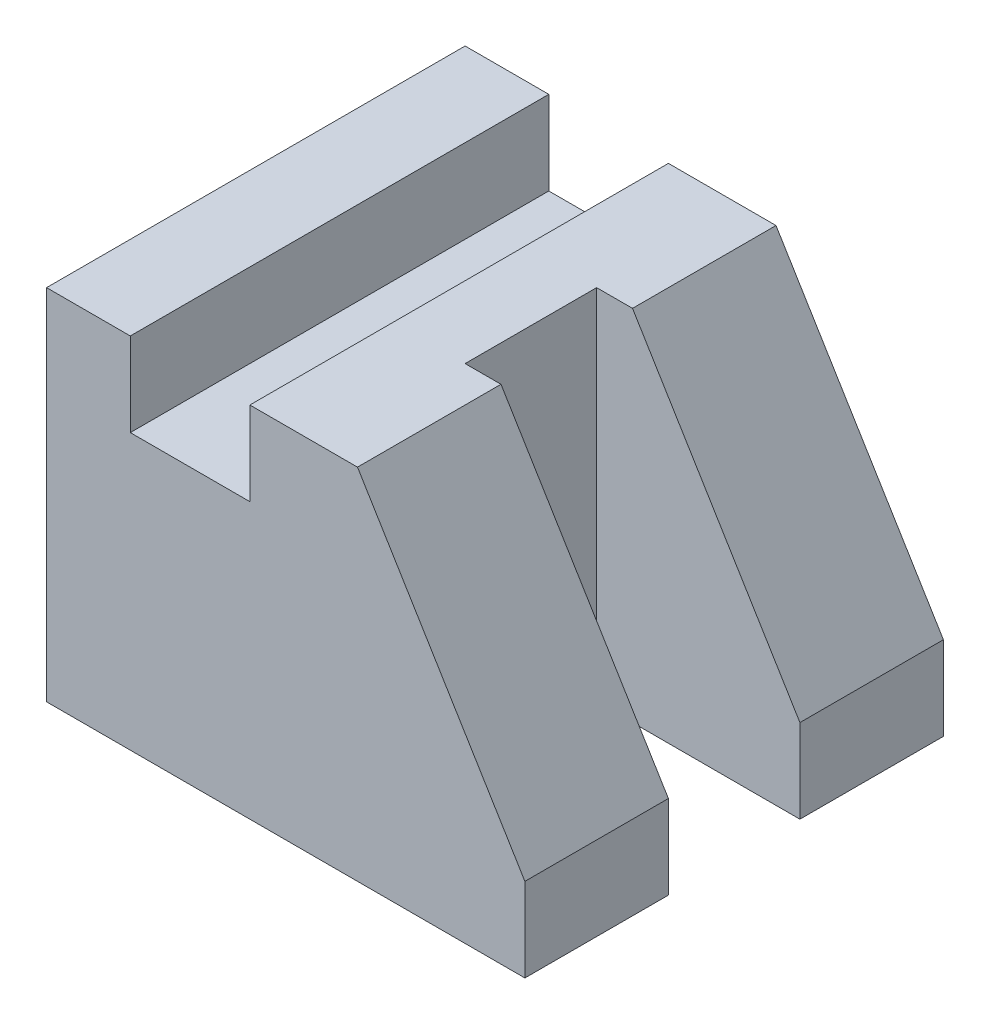
SolidWorks part; units mm, degrees
ref_plane "Ön Düzlem" through (0, 0, 0) normal (0, 0, 1) x (1, 0, 0)
ref_plane "Üst Düzlem" through (0, 0, 0) normal (0, 1, 0) x (1, 0, 0)
ref_plane "Sağ Düzlem" through (0, 0, 0) normal (1, 0, 0) x (0, 0, -1)
sketch "Çizim1" plane through (0, 0, 0) normal (0, 0, 1) x (1, 0, 0)
  line L0 (0, 0) -> (0, 60)
  line L1 (0, 60) -> (14, 60)
  line L2 (14, 60) -> (14, 46)
  line L3 (14, 46) -> (34, 46)
  line L4 (34, 46) -> (34, 60)
  line L5 (34, 60) -> (52, 60)
  line L6 (52, 60) -> (80, 14)
  line L7 (0, 0) -> (80, 0)
  line L8 (80, 0) -> (80, 14)
  point P3 (0, 0)
  dimension "D1" = 80
  dimension "D2" = 60
  dimension "D3" = 14
  dimension "D4" = 14
  dimension "D5" = 18
  dimension "D6" = 20
  dimension "D7" = 14
extrude "Yükseklik-Ekstrüzyon1" add sketch "Çizim1" against normal blind 70
sketch "Çizim2" plane through (0, 0, 0) normal (0, 1, 0) x (1, 0, 0)
  line L0 (80, 70) -> (46, 70)
  line L1 (46, 70) -> (0, 70)
  line L2 (0, 70) -> (0, 0)
  line L3 (0, 0) -> (80, 0)
  line L4 (80, 70) -> (80, 0) construction
  line L5 (80, 0) -> (52, 0) construction
  line L6 (80, 0) -> (80, 24)
  line L7 (80, 24) -> (46, 24)
  line L8 (46, 24) -> (46, 46)
  line L9 (46, 46) -> (80, 46)
  line L10 (80, 46) -> (80, 70)
  line L11 (52, 70) -> (52, 0) construction
  dimension "D1" = 24
  dimension "D2" = 24
  dimension "D3" = 6
extrude "Kes-Ekstrüzyon3" cut sketch "Çizim2" along normal up to surface (60 mm away) flip side to cut up to face at (43, 60, -35)
